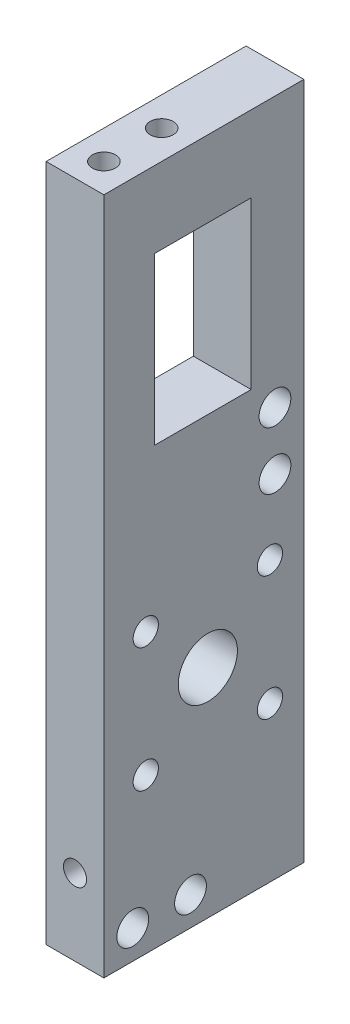
SolidWorks part; units mm, degrees
material "6061-T6 (SS)"
ref_plane "前视基准面" through (0, 0, 0) normal (0, 0, 1) x (1, 0, 0)
ref_plane "上视基准面" through (0, 0, 0) normal (0, 1, 0) x (1, 0, 0)
ref_plane "右视基准面" through (0, 0, 0) normal (1, 0, 0) x (0, 0, -1)
other "Configuration Table"
sketch "草图1" plane through (0, 0, 0) normal (0, 0, 1) x (1, 0, 0)
  line L1 (49.65, -4.3) -> (53.65, -4.3)
  line L2 (49.65, -4.3) -> (49.65, 42.68)
  line L3 (49.65, 42.68) -> (53.65, 42.68)
  line L4 (53.65, -4.3) -> (53.65, 42.68)
  dimension "D1" = 49.65
  dimension "D2" = 53.65
  dimension "D3" = 42.68
  dimension "D4" = 4.3
extrude "Main_Stock" add sketch "草图1" along normal blind 8.8519 from offset 2.2481
sketch "草图2" plane through (0, 0, 11.1) normal (0, 0, 1) x (1, 0, 0)
  circle A0 centre (51.65, 1) radius 0.8
  dimension "D1" = 1.6
  dimension "D2" = 51.65
  dimension "D3" = 1
extrude "Frame_1xD1p6_Through" cut sketch "草图2" against normal through all
cosmetic thread "Frame_M2_Through_Cosmetic_1" parameters "D2"=2
sketch "草图3" plane through (53.65, 0, 0) normal (1, 0, 0) x (0, 0, -1)
  circle A0 centre (-3.8995, 10.725) radius 2.05
  dimension "D1" = 4.1
  dimension "D2" = 3.8995
  dimension "D3" = 10.725
extrude "SMA_Center_D4p1" cut sketch "草图3" against normal blind 4
sketch "草图4" plane through (53.65, 0, 0) normal (1, 0, 0) x (0, 0, -1)
  circle A0 centre (-8.1995, 6.425) radius 0.875
  circle A1 centre (-8.1995, 15.025) radius 0.875
  dimension "D1" = 1.75
  dimension "D2" = 8.1995
  dimension "D3" = 6.425
  dimension "D4" = 15.025
extrude "SMA_Upper_2xD1p75_Through" cut sketch "草图4" against normal through all
cosmetic thread "SMA_Upper_Cosmetic_1" parameters "D2"=2.2
cosmetic thread "SMA_Upper_Cosmetic_2" parameters "D2"=2.2
sketch "草图5" plane through (53.65, 0, 0) normal (1, 0, 0) x (0, 0, -1)
  line L1 (-0.9, 25.9) -> (-7.6, 25.9)
  line L2 (-0.9, 25.9) -> (-0.9, 37.4)
  line L3 (-0.9, 37.4) -> (-7.6, 37.4)
  line L4 (-7.6, 25.9) -> (-7.6, 37.4)
  dimension "D1" = 0.9
  dimension "D2" = 7.6
  dimension "D3" = 25.9
  dimension "D4" = 37.4
extrude "TypeC_Window_11p5x6p7" cut sketch "草图5" against normal blind 4
sketch "草图6" plane through (53.65, 0, 0) normal (1, 0, 0) x (0, 0, -1)
  circle A0 centre (-5.1, -2.3) radius 1.1
  circle A1 centre (-9.1, -2.3) radius 1.1
  dimension "D1" = 2.2
  dimension "D2" = 5.1
  dimension "D3" = 9.1
  dimension "D4" = 2.3
extrude "Corner_Front_2xD2p2_Through" cut sketch "草图6" against normal through all
sketch "草图7" plane through (0, 42.68, 0) normal (0, 1, 0) x (1, 0, 0)
  circle A0 centre (51.65, -5.1) radius 0.8
  circle A1 centre (51.65, -9.1) radius 0.8
  dimension "D1" = 1.6
  dimension "D2" = 51.65
  dimension "D3" = 5.1
  dimension "D4" = 9.1
extrude "Corner_Rear_2xD1p6_Blind4" cut sketch "草图7" against normal blind 4
cosmetic thread "Corner_Rear_M2_Cosmetic_1" parameters "D1"=3.5, "D2"=2
cosmetic thread "Corner_Rear_M2_Cosmetic_2" parameters "D1"=3.5, "D2"=2
sketch "草图8" plane through (0, 0, 2.2481) normal (0, 0, -1) x (-1, 0, 0)
  line L1 (-49.65, -4.3) -> (-53.65, -4.3)
  line L2 (-49.65, -4.3) -> (-49.65, 42.68)
  line L3 (-49.65, 42.68) -> (-53.65, 42.68)
  line L4 (-53.65, -4.3) -> (-53.65, 42.68)
  dimension "D1" = 49.65
  dimension "D2" = 53.65
  dimension "D3" = 42.68
  dimension "D4" = 4.3
extrude "Wall_Extension_To_Floor" add sketch "草图8" along normal blind 5
sketch "草图9" plane through (53.65, 0, 0) normal (1, 0, 0) x (0, 0, -1)
  circle A0 centre (-3.8995, 10.725) radius 2.05
  dimension "D1" = 4.1
  dimension "D2" = 3.8995
  dimension "D3" = 10.725
extrude "SMA_Center_Full_Bore" cut sketch "草图9" against normal blind 4.01
sketch "草图10" plane through (53.65, 0, 0) normal (1, 0, 0) x (0, 0, -1)
  circle A0 centre (0.4005, 6.425) radius 0.875
  circle A1 centre (0.4005, 15.025) radius 0.875
  dimension "D1" = 1.75
  dimension "D2" = 0.4005
  dimension "D3" = 6.425
  dimension "D4" = 15.025
extrude "SMA_Lower_M2p2_Through" cut sketch "草图10" against normal blind 4.01
cosmetic thread "装饰螺纹线1" parameters "D2"=2.2
cosmetic thread "装饰螺纹线2" parameters "D2"=2.2
sketch "草图11" plane through (53.65, 0, 0) normal (1, 0, 0) x (0, 0, -1)
  line L1 (-0.9, 25.9) -> (-7.6, 25.9)
  line L2 (-0.9, 25.9) -> (-0.9, 37.4)
  line L3 (-0.9, 37.4) -> (-7.6, 37.4)
  line L4 (-7.6, 25.9) -> (-7.6, 37.4)
  dimension "D1" = 0.9
  dimension "D2" = 7.6
  dimension "D3" = 25.9
  dimension "D4" = 37.4
extrude "Right_Window_Full_11p5x6p7" cut sketch "草图11" against normal blind 4.01
sketch "草图12" plane through (53.65, 0, 0) normal (1, 0, 0) x (0, 0, -1)
  circle A0 centre (0.75, 20) radius 1.1
  circle A1 centre (0.75, 24) radius 1.1
  dimension "D1" = 2.2
  dimension "D2" = 0.75
  dimension "D3" = 20
  dimension "D4" = 24
extrude "Horizontal_Base_M2_0_0.05365" cut sketch "草图12" against normal blind 4.01
